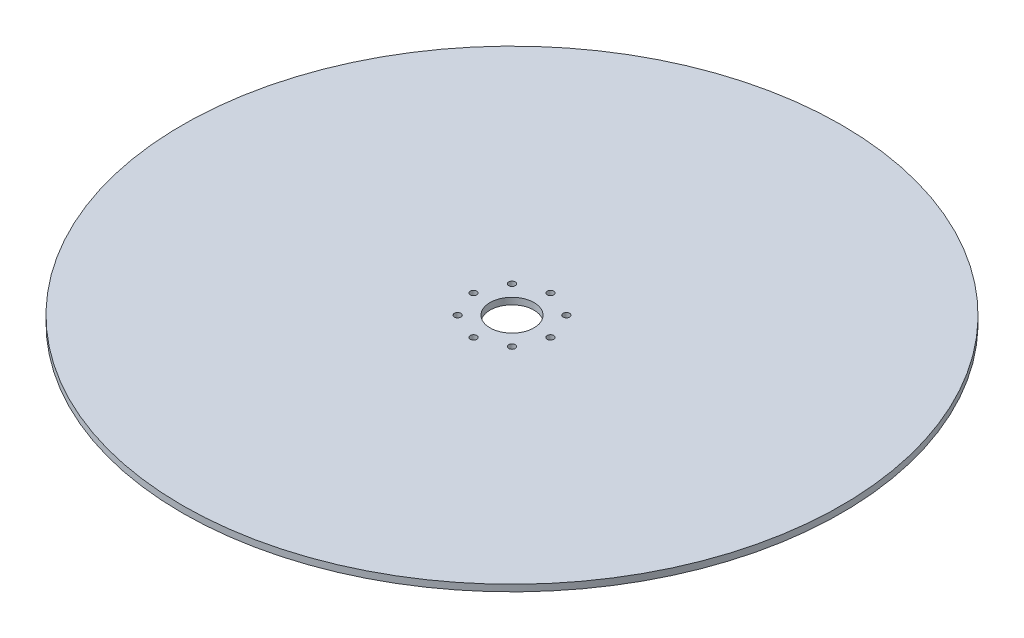
SolidWorks part; units mm, degrees
material "聚脂树脂"
ref_plane "前视基准面" through (0, 0, 0) normal (0, 0, 1) x (1, 0, 0)
ref_plane "上视基准面" through (0, 0, 0) normal (0, 1, 0) x (1, 0, 0)
ref_plane "右视基准面" through (0, 0, 0) normal (1, 0, 0) x (0, 0, -1)
other "Configuration Table"
sketch "草图1" plane through (0, 0, 0) normal (0, 1, 0) x (1, 0, 0)
  line L0 (0, 0) -> (0, 68.3524) construction
  line L1 (0, 0) -> (46.682, 46.682) construction
  line L2 (0, 0) -> (48.2557, 0) construction
  circle A0 centre (0, 0) radius 150
  circle A1 centre (0, 0) radius 10
  circle A2 centre (12.3744, 12.3744) radius 1.5
  circle A3 centre (-12.3744, 12.3744) radius 1.5
  circle A4 centre (0, 17.5) radius 1.5
  circle A5 centre (17.5, 0) radius 1.5
  circle A6 centre (12.3744, -12.3744) radius 1.5
  circle A7 centre (0, -17.5) radius 1.5
  circle A8 centre (-12.3744, -12.3744) radius 1.5
  circle A9 centre (-17.5, 0) radius 1.5
  dimension "D2" = 20
  dimension "D3" = 300
  dimension "D4" = 3
  dimension "D6" = 3
  dimension "D7" = 3
  dimension "D9" = 17.5
  dimension "D1" = 45
  dimension "D5" = 17.5
  dimension "D8" = 17.5
extrude "凸台-拉伸1" add sketch "草图1" along normal blind 3
